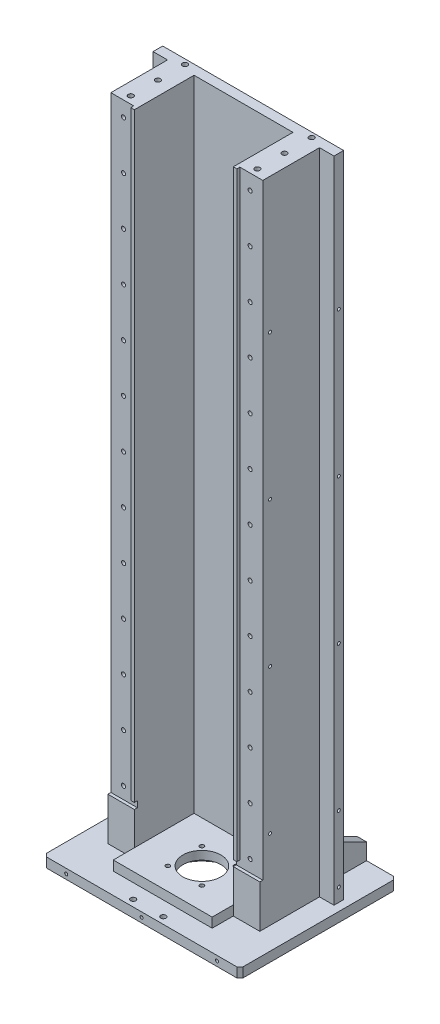
SolidWorks part; units mm, degrees
ref_plane "Front" through (0, 0, 0) normal (0, 0, 1) x (1, 0, 0)
ref_plane "Top" through (0, 0, 0) normal (0, 1, 0) x (1, 0, 0)
ref_plane "Right" through (0, 0, 0) normal (1, 0, 0) x (0, 0, -1)
sketch "Sketch1" plane through (0, 0, 0) normal (0, 1, 0) x (1, 0, 0)
  line L0 (0, -351.9173) -> (0, 56.9484) construction
  line L1 (-163, 0) -> (163, 0)
  line L2 (-163, 0) -> (-163, -260)
  line L3 (-163, -260) -> (163, -260)
  line L4 (163, 0) -> (163, -260)
  dimension "D1" = 260
  dimension "D2" = 326
extrude "Boss-Extrude1" add sketch "Sketch1" along normal blind 16
sketch "Sketch3" plane through (0, 0, 0) normal (0, 0, -1) x (-1, 0, 0)
  line L0 (-163, 16) -> (163, 16) construction
  line L1 (-150, 1092) -> (150, 1092)
  line L2 (-150, 1092) -> (-150, 16)
  line L3 (-150, 16) -> (150, 16)
  line L4 (150, 1092) -> (150, 16)
  line L5 (0, -49.0067) -> (0, 1337.4586) construction
  dimension "D1" = 1076
  dimension "D2" = 300
extrude "Boss-Extrude2" add sketch "Sketch3" against normal blind 16 from offset 75 separate body offset against normal yes
sketch "Sketch4" plane through (163, 0, 0) normal (1, 0, 0) x (0, 0, -1)
  line L1 (-91, 1092) -> (-190, 1092)
  line L2 (-91, 1092) -> (-91, 16)
  line L3 (-91, 16) -> (-190, 16)
  line L4 (-190, 1092) -> (-190, 16)
  line L6 (-260, 16) -> (-260, 0) construction
  dimension "D1" = 70
extrude "Boss-Extrude3" add sketch "Sketch4" against normal blind 44 from offset 37 separate body offset against normal yes
sketch "Sketch5" plane through (-163, 0, 0) normal (-1, 0, 0) x (0, 0, 1)
  line L4 (91, 1092) -> (91, 16)
  line L5 (91, 16) -> (190, 16)
  line L6 (190, 16) -> (190, 1092)
  line L7 (190, 1092) -> (91, 1092)
  line L8 (91, 1092) -> (91, 16)
  line L9 (91, 16) -> (190, 16)
  line L10 (190, 16) -> (190, 1092)
  line L11 (190, 1092) -> (91, 1092)
  dimension "D1" = 0
extrude "Boss-Extrude4" add sketch "Sketch5" against normal blind 44 from offset 37 separate body offset against normal yes
sketch "Sketch13" plane through (0, 16, 0) normal (0, 1, 0) x (1, 0, 0)
  line L0 (82, -91) -> (82, -190) construction
  line L1 (-82, -91) -> (82, -91)
  line L2 (-82, -91) -> (-82, -225)
  line L3 (-82, -225) -> (82, -225)
  line L4 (82, -91) -> (82, -225)
  line L6 (163, 0) -> (-163, 0) construction
  dimension "D1" = 225
extrude "Boss-Extrude7" add sketch "Sketch13" along normal blind 16 separate body
sketch "Sketch6" plane through (163, 0, 0) normal (1, 0, 0) x (0, 0, -1)
  line L0 (-75, 80) -> (0, 43)
  line L1 (-75, 1092) -> (-75, 16) construction
  line L2 (-75, 80) -> (-75, 16)
  line L3 (-75, 16) -> (0, 16)
  line L4 (0, 43) -> (0, 16)
  dimension "D1" = 27
  dimension "D2" = 37
extrude "Boss-Extrude5" add sketch "Sketch6" against normal blind 16 from offset 50 separate body offset against normal yes
sketch "Sketch7" plane through (-163, 0, 0) normal (-1, 0, 0) x (0, 0, 1)
  line L4 (0, 43) -> (0, 16)
  line L5 (0, 16) -> (75, 16)
  line L6 (75, 16) -> (75, 80)
  line L7 (75, 80) -> (0, 43)
  line L8 (0, 43) -> (0, 16)
  line L9 (0, 16) -> (75, 16)
  line L10 (75, 16) -> (75, 80)
  line L11 (75, 80) -> (0, 43)
  dimension "D1" = 0
extrude "Boss-Extrude6" add sketch "Sketch7" against normal blind 16 from offset 50 separate body offset against normal yes
combine bodies "Combine1" operation type add bodies to combine 104 102 103 101 106 107 112
sketch "Sketch8" plane through (0, 0, 190) normal (0, 0, 1) x (1, 0, 0)
  line L0 (126, 87) -> (82, 87)
  line L1 (126, 1092) -> (88, 1092)
  line L2 (126, 1092) -> (126, 87)
  line L3 (82, 87) -> (82, 97)
  line L4 (88, 1092) -> (88, 97)
  line L5 (-163, 0) -> (163, 0) construction
  line L6 (-126, 1092) -> (-88, 1092)
  line L7 (-126, 1092) -> (-126, 87)
  line L8 (-126, 87) -> (-82, 87)
  line L9 (-88, 1092) -> (-88, 97)
  line L10 (0, -52.6972) -> (0, 908.8253) construction
  line L12 (88, 97) -> (82, 97)
  line L13 (82, 32) -> (82, 1092) construction
  line L14 (-82, 1092) -> (-82, 32) construction
  line L15 (-82, 87) -> (-82, 97)
  line L16 (-82, 97) -> (-88, 97)
  dimension "D1" = 176
  dimension "D2" = 87
  dimension "D3" = 10
extrude "Cut-Extrude1" cut sketch "Sketch8" against normal blind 5
sketch "Sketch14" plane through (0, 0, 0) normal (0, -1, 0) x (1, 0, 0)
  line L0 (163, 0) -> (-163, 0) construction
  circle A0 centre (0, 160) radius 31.5
  dimension "D1" = 63
  dimension "D2" = 160
extrude "Cut-Extrude2" cut sketch "Sketch14" against normal up to next
sketch "Sketch15" plane through (0, 0, 0) normal (0, -1, 0) x (1, 0, 0)
  circle A0 centre (0, 160) radius 55
  dimension "D1" = 110
extrude "Cut-Extrude3" cut sketch "Sketch15" against normal blind 18
hole_wizard "M10x1.5 Tapped Hole1" positions "Sketch10" profile "Sketch9" tap size "M10x1.5" standard "JIS"
sketch "Sketch10" plane through (0, 1092, 0) normal (0, 1, 0) x (-1, 0, 0)
  line L2 (0, -11.9541) -> (0, 141.8463) construction
  line L5 (-97, 0) -> (97, 0) construction
  point P0 (-105, 83)
  point P1 (105, 83)
  dimension "D1" = 210
  dimension "D2" = 83
sketch "Sketch9" plane through (105, 1092, 83) normal (1, 0, 0) x (0, 0, 1)
  line L0 (0, 0) -> (0, 27.0537)
  line L1 (0, 27.0537) -> (4.25, 24.5)
  line L2 (4.25, 24.5) -> (4.25, 0)
  line L5 (4.25, 0) -> (0, 0)
  line L10 (0, 27.0537) -> (-4.25, 24.5) construction
  line L11 (0, -6.35) -> (0, 107.95) construction
  dimension "Tap Drill Dia." = 8.5
  dimension "Tap Drill Depth" = 24.5
  dimension "Drill Angle" = 118
cosmetic thread "Hole Thread3" parameters "D1"=20, "D2"=10
cosmetic thread "Hole Thread4" parameters "D1"=20, "D2"=10
pattern_linear "LPattern1" count 3 spacing 45 along (0, 0, 1) of "M10x1.5 Tapped Hole1"
hole_wizard "M10x1.5 Tapped Hole2" positions "Sketch12" profile "Sketch11" tap size "M10x1.5" standard "JIS" end condition up to next
sketch "Sketch12" plane through (0, 0, 0) normal (0, -1, 0) x (1, 0, 0)
  line L0 (0, -8.0783) -> (0, 295.5188) construction
  line L2 (163, 0) -> (-163, 0) construction
  line L3 (-163, 260) -> (163, 260) construction
  point P1 (-25, 249)
  point P3 (25, 249)
  dimension "D1" = 249
  dimension "D2" = 50
sketch "Sketch11" plane through (-25, 0, 249) normal (1, 0, 0) x (0, 0, -1)
  line L0 (0, 0) -> (0, 16)
  line L1 (0, 16) -> (4.25, 16)
  line L2 (4.25, 16) -> (4.25, 0)
  line L5 (4.25, 0) -> (0, 0)
  line L11 (0, -6.35) -> (0, 107.95) construction
  dimension "Thru Tap Drill Dia." = 8.5
  dimension "Thru Tap Drill Depth" = 16
cosmetic thread "Hole Thread5" parameters "D2"=10
cosmetic thread "Hole Thread6" parameters "D2"=10
hole_wizard "M8x1.25 Tapped Hole1" positions "Sketch17" profile "Sketch16" tap size "M8x1.25" standard "JIS" end condition up to next
sketch "Sketch17" plane through (0, 0, 0) normal (0, -1, 0) x (1, 0, 0)
  line L0 (0, 160) -> (40, 160) construction
  line L2 (0, 160) -> (28.2843, 188.2843) construction
  circle A0 centre (0, 160) radius 40 construction
  point P1 (-28.2843, 188.2843)
  point P3 (28.2843, 188.2843)
  point P5 (28.2843, 131.7157)
  point P7 (-28.2843, 131.7157)
  dimension "D1" = 80
  dimension "D2" = 45
sketch "Sketch16" plane through (-28.2843, 0, 188.2843) normal (1, 0, 0) x (0, 0, -1)
  line L0 (0, 0) -> (0, 32)
  line L1 (0, 32) -> (3.4, 32)
  line L2 (3.4, 32) -> (3.4, 0)
  line L5 (3.4, 0) -> (0, 0)
  line L11 (0, -6.35) -> (0, 107.95) construction
  dimension "Thru Tap Drill Dia." = 6.8
  dimension "Thru Tap Drill Depth" = 32
cosmetic thread "Hole Thread7" parameters "D2"=8
cosmetic thread "Hole Thread8" parameters "D2"=8
cosmetic thread "Hole Thread9" parameters "D2"=8
cosmetic thread "Hole Thread10" parameters "D2"=8
hole_wizard "M8x1.25 Tapped Hole2" positions "Sketch19" profile "Sketch18" tap size "M8x1.25" standard "JIS"
sketch "Sketch19" plane through (0, 0, 185) normal (0, 0, 1) x (1, 0, 0)
  line L0 (0, -14.2068) -> (0, 194.2898) construction
  line L1 (-163, 0) -> (163, 0) construction
  point P0 (105, 107)
  point P1 (-105, 107)
  dimension "D1" = 210
  dimension "D2" = 107
sketch "Sketch18" plane through (105, 107, 185) normal (1, 0, 0) x (0, -1, 0)
  line L0 (0, 0) -> (0, 21.7929)
  line L1 (0, 21.7929) -> (3.4, 19.75)
  line L2 (3.4, 19.75) -> (3.4, 0)
  line L5 (3.4, 0) -> (0, 0)
  line L10 (0, 21.7929) -> (-3.4, 19.75) construction
  line L11 (0, -6.35) -> (0, 107.95) construction
  dimension "Tap Drill Dia." = 6.8
  dimension "Tap Drill Depth" = 19.75
  dimension "Drill Angle" = 118
cosmetic thread "Hole Thread11" parameters "D1"=19.75, "D2"=8
cosmetic thread "Hole Thread12" parameters "D1"=19.75, "D2"=8
pattern_linear "LPattern2" count 13 spacing 80 along (0, 1, 0) of "M8x1.25 Tapped Hole2"
hole_wizard "M6x1.0 Tapped Hole1" positions "Sketch21" profile "Sketch20" tap size "M6x1.0" standard "JIS"
sketch "Sketch21" plane through (0, 0, 260) normal (0, 0, 1) x (1, 0, 0)
  line L0 (0, -14.0636) -> (0, 68.6643) construction
  line L2 (-163, 0) -> (163, 0) construction
  point P0 (125, 8)
  point P1 (-125, 8)
  point P11 (0, 8)
  dimension "D1" = 250
  dimension "D2" = 8
sketch "Sketch20" plane through (125, 8, 260) normal (1, 0, 0) x (0, -1, 0)
  line L0 (0, 0) -> (0, 16.5022)
  line L1 (0, 16.5022) -> (2.5, 15)
  line L2 (2.5, 15) -> (2.5, 0)
  line L5 (2.5, 0) -> (0, 0)
  line L10 (0, 16.5022) -> (-2.5, 15) construction
  line L11 (0, -6.35) -> (0, 107.95) construction
  dimension "Tap Drill Dia." = 5
  dimension "Tap Drill Depth" = 15
  dimension "Drill Angle" = 118
cosmetic thread "Hole Thread13" parameters "D1"=12, "D2"=6
cosmetic thread "Hole Thread14" parameters "D1"=12, "D2"=6
cosmetic thread "Hole Thread24" parameters "D1"=12, "D2"=6
hole_wizard "M6x1.0 Tapped Hole2" positions "Sketch23" profile "Sketch22" tap size "M6x1.0" standard "JIS"
sketch "Sketch23" plane through (126, 0, 0) normal (1, 0, 0) x (0, 0, -1)
  line L0 (0, 16) -> (0, 43) construction
  line L1 (-260, 0) -> (0, 0) construction
  point P0 (-173, 148)
  point P1 (-173, 388)
  point P3 (-173, 628)
  point P5 (-173, 868)
  dimension "D1" = 173
  dimension "D2" = 148
  dimension "D3" = 240
  dimension "D4" = 240
  dimension "D5" = 240
sketch "Sketch22" plane through (126, 148, 173) normal (0, 1, 0) x (0, 0, -1)
  line L0 (0, 0) -> (0, 16.5022)
  line L1 (0, 16.5022) -> (2.5, 15)
  line L2 (2.5, 15) -> (2.5, 0)
  line L5 (2.5, 0) -> (0, 0)
  line L10 (0, 16.5022) -> (-2.5, 15) construction
  line L11 (0, -6.35) -> (0, 107.95) construction
  dimension "Tap Drill Dia." = 5
  dimension "Tap Drill Depth" = 15
  dimension "Drill Angle" = 118
cosmetic thread "Hole Thread15" parameters "D1"=12, "D2"=6
cosmetic thread "Hole Thread16" parameters "D1"=12, "D2"=6
cosmetic thread "Hole Thread17" parameters "D1"=12, "D2"=6
cosmetic thread "Hole Thread18" parameters "D1"=12, "D2"=6
hole_wizard "M6x1.0 Tapped Hole3" positions "Sketch25" profile "Sketch24" tap size "M6x1.0" standard "JIS"
sketch "Sketch25" plane through (150, 0, 0) normal (1, 0, 0) x (0, 0, -1)
  line L0 (-260, 0) -> (0, 0) construction
  line L1 (0, 16) -> (0, 43) construction
  point P0 (-83, 38)
  dimension "D1" = 38
  dimension "D2" = 83
sketch "Sketch24" plane through (150, 38, 83) normal (0, 1, 0) x (0, 0, -1)
  line L0 (0, 0) -> (0, 16.5022)
  line L1 (0, 16.5022) -> (2.5, 15)
  line L2 (2.5, 15) -> (2.5, 0)
  line L5 (2.5, 0) -> (0, 0)
  line L10 (0, 16.5022) -> (-2.5, 15) construction
  line L11 (0, -6.35) -> (0, 107.95) construction
  dimension "Tap Drill Dia." = 5
  dimension "Tap Drill Depth" = 15
  dimension "Drill Angle" = 118
cosmetic thread "Hole Thread19" parameters "D1"=12, "D2"=6
hole_wizard "M6x1.0 Tapped Hole4" positions "Sketch27" profile "Sketch26" tap size "M6x1.0" standard "JIS"
sketch "Sketch27" plane through (150, 0, 0) normal (1, 0, 0) x (0, 0, -1)
  point P0 (-83, 148)
  point P4 (-83, 388)
  point P6 (-83, 628)
  point P8 (-83, 868)
sketch "Sketch26" plane through (150, 148, 83) normal (0, 1, 0) x (0, 0, -1)
  line L0 (0, 0) -> (0, 16.5022)
  line L1 (0, 16.5022) -> (2.5, 15)
  line L2 (2.5, 15) -> (2.5, 0)
  line L5 (2.5, 0) -> (0, 0)
  line L10 (0, 16.5022) -> (-2.5, 15) construction
  line L11 (0, -6.35) -> (0, 107.95) construction
  dimension "Tap Drill Dia." = 5
  dimension "Tap Drill Depth" = 15
  dimension "Drill Angle" = 118
cosmetic thread "Hole Thread20" parameters "D1"=12, "D2"=6
cosmetic thread "Hole Thread21" parameters "D1"=12, "D2"=6
cosmetic thread "Hole Thread22" parameters "D1"=12, "D2"=6
cosmetic thread "Hole Thread23" parameters "D1"=12, "D2"=6
mirror "Mirror1" about plane through (0, 0, 0) normal (1, 0, 0) of "M6x1.0 Tapped Hole4", "M6x1.0 Tapped Hole3", "M6x1.0 Tapped Hole2"
chamfer "Chamfer1" distance 5 angle 45 4 edges at (-163, 8, 0) (-163, 8, 260) (163, 8, 0) (163, 8, 260)
